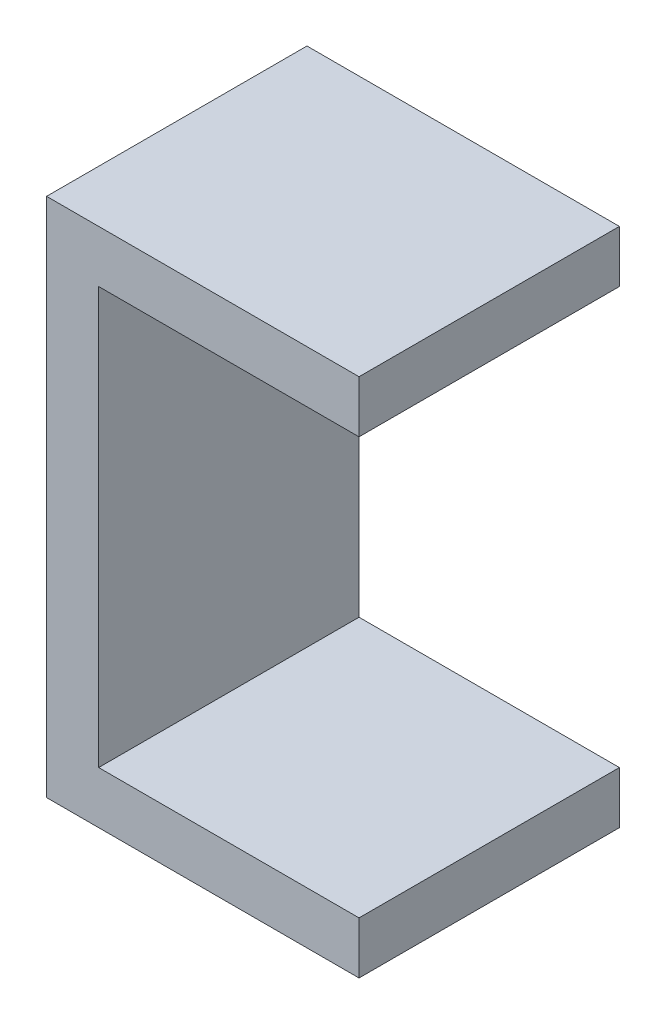
SolidWorks part; units mm, degrees
ref_plane "Piano frontale" through (0, 0, 0) normal (0, 0, 1) x (1, 0, 0)
ref_plane "Piano superiore" through (0, 0, 0) normal (0, 1, 0) x (1, 0, 0)
ref_plane "Piano destro" through (0, 0, 0) normal (1, 0, 0) x (0, 0, -1)
sketch "Schizzo1" plane through (0, 0, 0) normal (0, 0, 1) x (1, 0, 0)
  line L0 (0, 10) -> (0, -10)
  line L1 (0, -10) -> (12, -10)
  line L2 (12, -10) -> (12, -8)
  line L3 (12, -8) -> (2, -8)
  line L4 (2, -8) -> (2, 8)
  line L5 (55, 0) -> (-55, 0) construction
  line L6 (12, 10) -> (12, 8)
  line L7 (0, 10) -> (12, 10)
  line L8 (12, 8) -> (2, 8)
  point P0 (-11.6775, 5.3328)
  point P7 (0, 0)
  point P13 (2, 0)
  dimension "D1" = 8
  dimension "D2" = 2
  dimension "D3" = 12
  dimension "D4" = 2
extrude "Estrusione-Estrusione1" add sketch "Schizzo1" along normal blind 10
